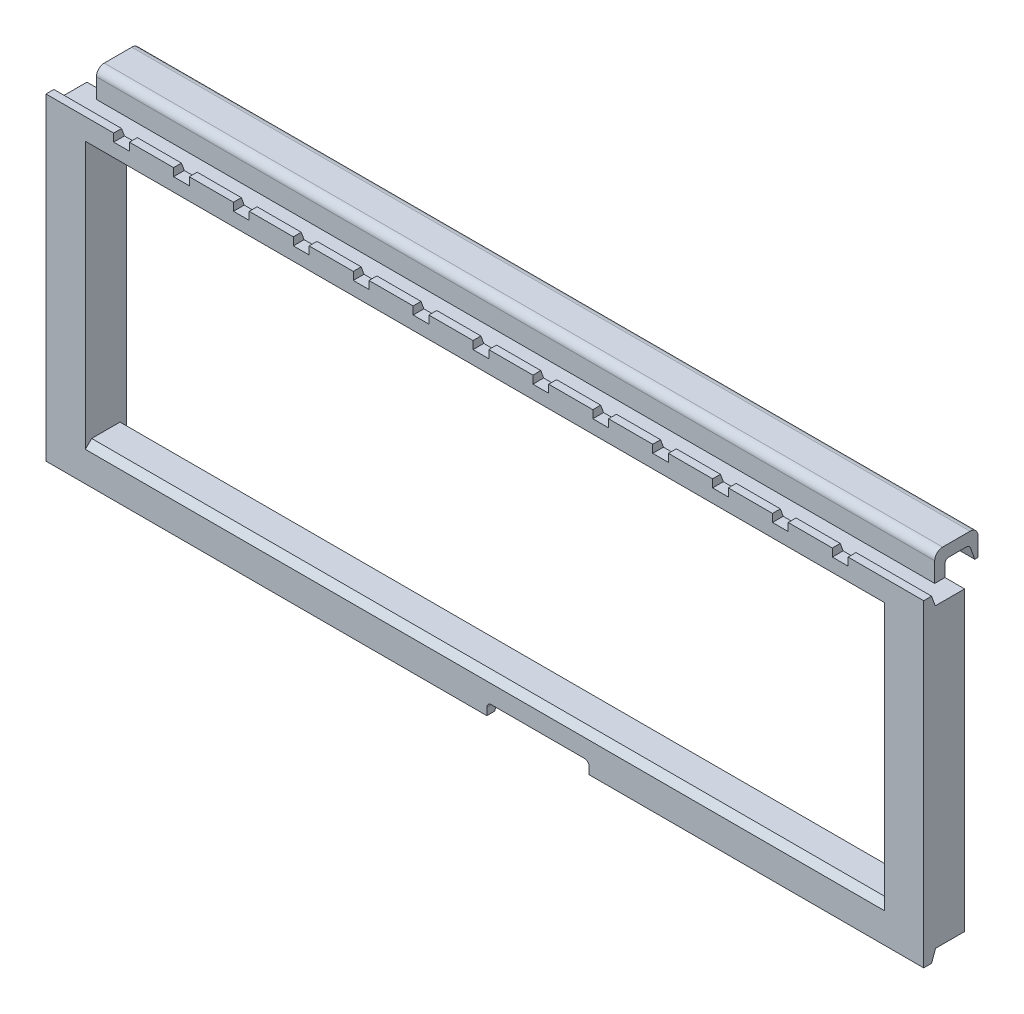
SolidWorks part; units mm, degrees
material "S235JRG2"
ref_plane "Front Plane" through (0, 0, 0) normal (0, 0, 1) x (1, 0, 0)
ref_plane "Top Plane" through (0, 0, 0) normal (0, 1, 0) x (1, 0, 0)
ref_plane "Right Plane" through (0, 0, 0) normal (1, 0, 0) x (0, 0, -1)
sketch "Sketch1" plane through (0, 0, 0) normal (1, 0, 0) x (0, 0, -1)
  line L0 (0, 0) -> (0, 46)
  line L1 (0, 46) -> (52, 46)
  line L2 (52, 46) -> (52, 14)
  line L3 (52, 14) -> (15.0956, 14)
  line L4 (15.0956, 14) -> (10, 0)
  line L5 (10, 0) -> (0, 0)
  dimension "D1" = 52
  dimension "D2" = 46
  dimension "D3" = 14
  dimension "D4" = 20
  dimension "D5" = 10
extrude "Boss-Extrude1" add sketch "Sketch1" along normal mid plane 1115
sketch "Sketch2" plane through (0, 46, 0) normal (0, 1, 0) x (1, 0, 0)
  line L0 (557.5, 52) -> (-557.5, 52) construction
  line L1 (-557.5, 52) -> (-507.5, 52)
  line L2 (-557.5, 52) -> (-557.5, 0)
  line L3 (-557.5, 0) -> (-507.5, 0)
  line L4 (-507.5, 52) -> (-507.5, 0)
  line L5 (557.5, 0) -> (-557.5, 0) construction
  line L7 (0, 0) -> (0, 78.0192) construction
  line L8 (507.5, 52) -> (507.5, 0)
  line L9 (557.5, 0) -> (507.5, 0)
  line L10 (557.5, 52) -> (557.5, 0)
  line L11 (557.5, 52) -> (507.5, 52)
  point P8 (-557.5, 52)
  dimension "D1" = 50
extrude "Boss-Extrude2" add sketch "Sketch2" along normal blind 323
sketch "Sketch3" plane through (557.5, 0, 0) normal (1, 0, 0) x (0, 0, -1)
  line L0 (0, 369) -> (0, 404)
  line L1 (0, 404) -> (10, 404)
  line L2 (10, 404) -> (14.7316, 391)
  line L3 (14.7316, 391) -> (52, 391)
  line L4 (52, 391) -> (52, 369)
  line L5 (52, 369) -> (0, 369)
  dimension "D1" = 35
  dimension "D2" = 10
  dimension "D3" = 20
  dimension "D4" = 13
extrude "Boss-Extrude3" add sketch "Sketch3" against normal up to surface (1115 mm away)
sketch "Sketch4" plane through (0, 0, 0) normal (0, 0, 1) x (1, 0, 0)
  line L0 (557.5, 0) -> (-557.5, 0) construction
  line L1 (2.5, 0) -> (132.5, 0)
  line L2 (2.5, 0) -> (2.5, 15)
  line L3 (2.5, 15) -> (132.5, 15)
  line L4 (132.5, 0) -> (132.5, 15)
  line L6 (-557.5, 404) -> (-557.5, 0) construction
  dimension "D1" = 690
  dimension "D2" = 15
  dimension "D3" = 560
extrude "Cut-Extrude1" cut sketch "Sketch4" against normal through all
fillet "Fillet1" radius 6 2 edges at (132.5, 15, -26) (2.5, 15, -26)
sketch "Sketch5" plane through (0, 0, -52) normal (0, 0, -1) x (-1, 0, 0)
  line L0 (182.5, 52) -> (424.5, 52)
  line L1 (424.5, 52) -> (424.5, -46)
  line L2 (424.5, -46) -> (408.5, -46)
  line L3 (408.5, -46) -> (372.25, -83)
  line L4 (372.25, -83) -> (234.75, -83)
  line L5 (234.75, -83) -> (198.5, -46)
  line L6 (198.5, -46) -> (182.5, -46)
  line L7 (182.5, -46) -> (182.5, 52)
  line L8 (198.5, -46) -> (408.5, -46) construction
  line L9 (303.5, -83) -> (303.5, -46) construction
  line L10 (0, 0) -> (0, 150.938) construction
  line L11 (-507.5, 46) -> (507.5, 46) construction
  line L12 (303.5, -46) -> (303.5, 52) construction
  line L13 (-303.5, -46) -> (-303.5, 52) construction
  line L14 (-303.5, -83) -> (-303.5, -46) construction
  line L15 (-198.5, -46) -> (-408.5, -46) construction
  line L16 (-182.5, -46) -> (-182.5, 52)
  line L17 (-198.5, -46) -> (-182.5, -46)
  line L18 (-234.75, -83) -> (-198.5, -46)
  line L19 (-372.25, -83) -> (-234.75, -83)
  line L20 (-408.5, -46) -> (-372.25, -83)
  line L21 (-424.5, -46) -> (-408.5, -46)
  line L22 (-424.5, 52) -> (-424.5, -46)
  line L23 (-182.5, 52) -> (-424.5, 52)
  dimension "D1" = 365
  dimension "D2" = 242
  dimension "D3" = 98
  dimension "D4" = 6
  dimension "D5" = 135
  dimension "D6" = 137.5
  dimension "D7" = 210
extrude "Boss-Extrude4" [suppressed] add sketch "Sketch5" along normal blind 15
fillet "Fillet2" [suppressed] radius 10
sketch "Sketch6" [suppressed] plane through (0, 0, -55) normal (0, 0, -1) x (-1, 0, 0)
  line L0 (238.9522, -46) -> (368.0478, -46) construction
  line L1 (239.5, -8) -> (367.5, -8)
  line L2 (239.5, -8) -> (239.5, -46)
  line L3 (239.5, -46) -> (367.5, -46)
  line L4 (367.5, -8) -> (367.5, -46)
  line L5 (239.5, -8) -> (367.5, -46) construction
  line L6 (239.5, -46) -> (367.5, -8) construction
  point P0 (303.5, -27)
  point P7 (303.5, -46)
  dimension "D1" = 128
  dimension "D2" = 38
extrude "Boss-Extrude5" [suppressed] add sketch "Sketch6" along normal blind 25
sketch "Sketch7" [suppressed] plane through (0, 0, -80) normal (0, 0, -1) x (-1, 0, 0)
  line L0 (303.5, -46) -> (303.5, -8) construction
  line L1 (239.5, -46) -> (367.5, -46) construction
  line L2 (367.5, -8) -> (239.5, -8) construction
  line L3 (303.5, -27) -> (258.5, -27) construction
  circle A0 centre (258.5, -27) radius 10
  circle A1 centre (348.5, -27) radius 10
  dimension "D1" = 20
  dimension "D2" = 45
extrude "Cut-Extrude2" [suppressed] cut sketch "Sketch7" against normal through all
mirror "Mirror1" [suppressed] about plane through (0, 0, 0) normal (1, 0, 0)
sketch "Sketch8" plane through (0, 0, 0) normal (0, 0, 1) x (1, 0, 0)
  line L0 (-557.5, 404) -> (557.5, 404) construction
  line L1 (-471.5, 404) -> (-451.5, 404)
  line L2 (-471.5, 404) -> (-471.5, 394)
  line L3 (-471.5, 394) -> (-451.5, 394)
  line L4 (-451.5, 404) -> (-451.5, 394)
  line L5 (-557.5, 404) -> (-557.5, 0) construction
  line L6 (-395.4167, 404) -> (-375.4167, 404)
  line L7 (-395.4167, 404) -> (-395.4167, 394)
  line L8 (-395.4167, 394) -> (-375.4167, 394)
  line L9 (-375.4167, 404) -> (-375.4167, 394)
  line L10 (-319.3333, 404) -> (-299.3333, 404)
  line L11 (-319.3333, 404) -> (-319.3333, 394)
  line L12 (-319.3333, 394) -> (-299.3333, 394)
  line L13 (-299.3333, 404) -> (-299.3333, 394)
  line L14 (-243.25, 404) -> (-223.25, 404)
  line L15 (-243.25, 404) -> (-243.25, 394)
  line L16 (-243.25, 394) -> (-223.25, 394)
  line L17 (-223.25, 404) -> (-223.25, 394)
  line L18 (-167.1667, 404) -> (-147.1667, 404)
  line L19 (-167.1667, 404) -> (-167.1667, 394)
  line L20 (-167.1667, 394) -> (-147.1667, 394)
  line L21 (-147.1667, 404) -> (-147.1667, 394)
  line L22 (-91.0833, 404) -> (-71.0833, 404)
  line L23 (-91.0833, 404) -> (-91.0833, 394)
  line L24 (-91.0833, 394) -> (-71.0833, 394)
  line L25 (-71.0833, 404) -> (-71.0833, 394)
  line L26 (-15, 404) -> (5, 404)
  line L27 (-15, 404) -> (-15, 394)
  line L28 (-15, 394) -> (5, 394)
  line L29 (5, 404) -> (5, 394)
  line L30 (61.0833, 404) -> (81.0833, 404)
  line L31 (61.0833, 404) -> (61.0833, 394)
  line L32 (61.0833, 394) -> (81.0833, 394)
  line L33 (81.0833, 404) -> (81.0833, 394)
  line L34 (137.1667, 404) -> (157.1667, 404)
  line L35 (137.1667, 404) -> (137.1667, 394)
  line L36 (137.1667, 394) -> (157.1667, 394)
  line L37 (157.1667, 404) -> (157.1667, 394)
  line L38 (213.25, 404) -> (233.25, 404)
  line L39 (213.25, 404) -> (213.25, 394)
  line L40 (213.25, 394) -> (233.25, 394)
  line L41 (233.25, 404) -> (233.25, 394)
  line L42 (289.3333, 404) -> (309.3333, 404)
  line L43 (289.3333, 404) -> (289.3333, 394)
  line L44 (289.3333, 394) -> (309.3333, 394)
  line L45 (309.3333, 404) -> (309.3333, 394)
  line L46 (365.4167, 404) -> (385.4167, 404)
  line L47 (365.4167, 404) -> (365.4167, 394)
  line L48 (365.4167, 394) -> (385.4167, 394)
  line L49 (385.4167, 404) -> (385.4167, 394)
  line L50 (441.5, 404) -> (461.5, 404)
  line L51 (441.5, 404) -> (441.5, 394)
  line L52 (441.5, 394) -> (461.5, 394)
  line L53 (461.5, 404) -> (461.5, 394)
  line L54 (557.5, 404) -> (557.5, 0) construction
  dimension "D1" = 20
  dimension "D2" = 10
  dimension "D3" = 86
  dimension "D5" = 96
  dimension "D4" = 13
extrude "Cut-Extrude3" cut sketch "Sketch8" against normal through all
sketch "Sketch10" plane through (0, 0, -52) normal (0, 0, -1) x (-1, 0, 0)
  line L0 (557.5, 391) -> (-557.5, 391) construction
  line L1 (-532.5, 391) -> (532.5, 391)
  line L2 (-532.5, 391) -> (-532.5, 426)
  line L3 (-532.5, 426) -> (532.5, 426)
  line L4 (532.5, 391) -> (532.5, 426)
  line L5 (557.5, 391) -> (-557.5, 391) construction
  line L6 (0, 0) -> (0, 391) construction
  point P6 (-507, 391)
  dimension "D1" = 1065
  dimension "D3" = 35
extrude "Boss-Extrude7" add sketch "Sketch10" against normal blind 13
sketch "Sketch11" plane through (0, 0, 0) normal (1, 0, 0) x (0, 0, -1)
  line L0 (39, 426) -> (94, 426)
  line L1 (39, 426) -> (39, 391) construction
  line L2 (94, 426) -> (94, 392)
  line L3 (94, 392) -> (90, 392)
  line L4 (90, 392) -> (83.0846, 411)
  line L5 (83.0846, 411) -> (39, 411)
  line L6 (39, 411) -> (39, 426)
  line L8 (39, 426) -> (52, 426) construction
  point P7 (39, 446)
  dimension "D1" = 55
  dimension "D2" = 4
  dimension "D3" = 15
  dimension "D4" = 20
  dimension "D5" = 34
extrude "Boss-Extrude8" add sketch "Sketch11" along normal mid plane 1065
fillet "Fillet3" radius 10 2 edges at (0, 426, -94) (0, 426, -39)
fillet "Fillet4" radius 5 2 edges at (0, 411, -83.0846) (0, 411, -52)
chamfer "Chamfer1" distance 8 angle 45 4 edges at (0, 46, -52) (0, 46, 0) (0, 369, 0) (0, 369, -52)
